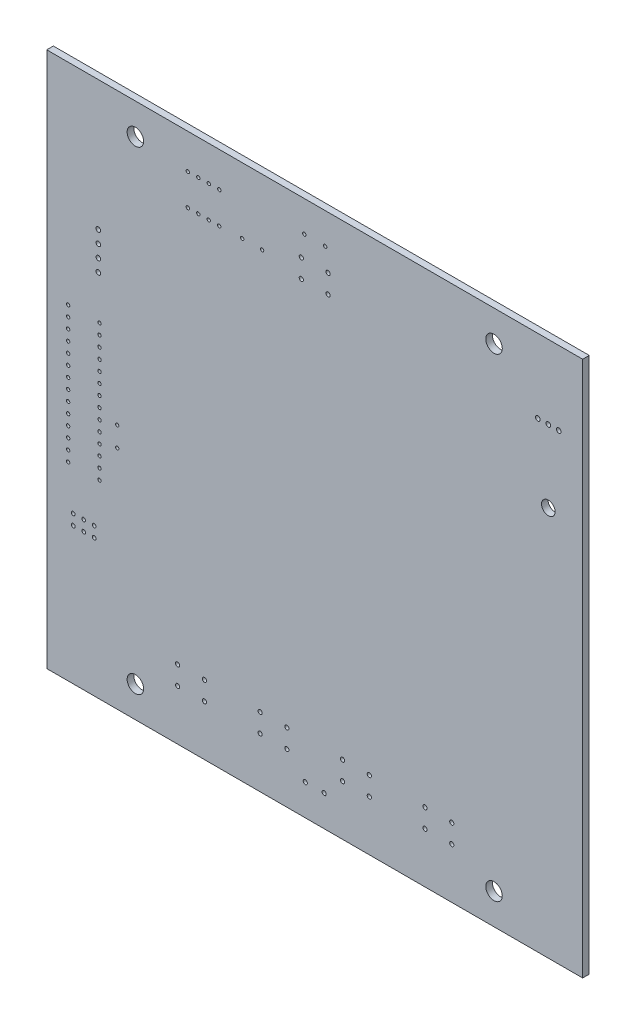
SolidWorks part; units mm, degrees
ref_plane "Ebene vorne" through (0, 0, 0) normal (0, 0, 1) x (1, 0, 0)
ref_plane "Ebene oben" through (0, 0, 0) normal (0, 1, 0) x (1, 0, 0)
ref_plane "Ebene rechts" through (0, 0, 0) normal (1, 0, 0) x (0, 0, -1)
ref_plane "Dielectric_Layer Layer 1" through (0, 0, 1.6) normal (0, 0, 1) x (1, 0, 0)
sketch "Skizze1" plane through (0, 0, 0) normal (0, 0, 1) x (1, 0, 0)
  line L0 (2.5, 2.5) -> (132.5, 2.5)
  line L1 (132.5, 2.5) -> (132.5, 132.5)
  line L2 (132.5, 132.5) -> (2.5, 132.5)
  line L3 (2.5, 132.5) -> (2.5, 2.5)
extrude "Board_Outline" add sketch "Skizze1" along normal blind 1.6 separate body
sketch "Skizze2" plane through (0, 0, 0) normal (0, 0, 1) x (1, 0, 0)
  circle A0 centre (24, 125) radius 2
  circle A1 centre (111, 10) radius 2
  circle A2 centre (24, 10) radius 2
  circle A3 centre (111, 125) radius 2
  circle A4 centre (124.17, 97.094) radius 1.651
extrude "NPTH" cut sketch "Skizze2" along normal through all
sketch "Skizze3" plane through (0, 0, 0) normal (0, 0, 1) x (1, 0, 0)
  circle A0 centre (15.31, 81.51) radius 0.405
  circle A1 centre (15.31, 78.97) radius 0.405
  circle A2 centre (15.31, 76.43) radius 0.405
  circle A3 centre (15.31, 73.89) radius 0.405
  circle A4 centre (15.31, 71.35) radius 0.405
  circle A5 centre (15.31, 68.81) radius 0.405
  circle A6 centre (15.31, 66.27) radius 0.405
  circle A7 centre (15.31, 63.73) radius 0.405
  circle A8 centre (15.31, 61.19) radius 0.405
  circle A9 centre (15.31, 58.65) radius 0.405
  circle A10 centre (15.31, 56.11) radius 0.405
  circle A11 centre (15.31, 53.57) radius 0.405
  circle A12 centre (15.31, 51.03) radius 0.405
  circle A13 centre (15.31, 48.49) radius 0.405
  circle A14 centre (7.69, 48.49) radius 0.405
  circle A15 centre (7.69, 51.03) radius 0.405
  circle A16 centre (7.69, 53.57) radius 0.405
  circle A17 centre (7.69, 56.11) radius 0.405
  circle A18 centre (7.69, 58.65) radius 0.405
  circle A19 centre (7.69, 61.19) radius 0.405
  circle A20 centre (7.69, 63.73) radius 0.405
  circle A21 centre (7.69, 66.27) radius 0.405
  circle A22 centre (7.69, 68.81) radius 0.405
  circle A23 centre (7.69, 71.35) radius 0.405
  circle A24 centre (7.69, 73.89) radius 0.405
  circle A25 centre (7.69, 76.43) radius 0.405
  circle A26 centre (7.69, 78.97) radius 0.405
  circle A27 centre (7.69, 81.51) radius 0.405
  circle A28 centre (64.96, 125) radius 0.405
  circle A29 centre (70.04, 125) radius 0.405
  circle A30 centre (15.01, 92) radius 0.56
  circle A31 centre (15, 101) radius 0.56
  circle A32 centre (15.02, 95) radius 0.56
  circle A33 centre (15.01, 98.01) radius 0.56
  circle A34 centre (19.59, 62.2) radius 0.405
  circle A35 centre (19.59, 57.38) radius 0.405
  circle A36 centre (121.63, 114.62) radius 0.56
  circle A37 centre (124.17, 114.62) radius 0.56
  circle A38 centre (126.71, 114.62) radius 0.56
  circle A39 centre (54.74, 116.59) radius 0.405
  circle A40 centre (49.92, 116.59) radius 0.405
  circle A41 centre (44.34, 116.42) radius 0.405
  circle A42 centre (41.8, 116.42) radius 0.405
  circle A43 centre (39.26, 116.42) radius 0.405
  circle A44 centre (36.72, 116.42) radius 0.405
  circle A45 centre (36.72, 124.04) radius 0.405
  circle A46 centre (39.26, 124.04) radius 0.405
  circle A47 centre (41.8, 124.04) radius 0.405
  circle A48 centre (44.34, 124.04) radius 0.405
  circle A49 centre (70.75, 119.76) radius 0.51
  circle A50 centre (64.25, 119.76) radius 0.51
  circle A51 centre (70.75, 115.24) radius 0.51
  circle A52 centre (64.25, 115.24) radius 0.51
  circle A53 centre (34.25, 14.74) radius 0.51
  circle A54 centre (40.75, 14.74) radius 0.51
  circle A55 centre (34.25, 19.26) radius 0.51
  circle A56 centre (40.75, 19.26) radius 0.51
  circle A57 centre (54.25, 14.74) radius 0.51
  circle A58 centre (60.75, 14.74) radius 0.51
  circle A59 centre (54.25, 19.26) radius 0.51
  circle A60 centre (60.75, 19.26) radius 0.51
  circle A61 centre (74.25, 14.74) radius 0.51
  circle A62 centre (80.75, 14.74) radius 0.51
  circle A63 centre (74.25, 19.26) radius 0.51
  circle A64 centre (80.75, 19.26) radius 0.51
  circle A65 centre (94.25, 14.74) radius 0.51
  circle A66 centre (100.75, 14.74) radius 0.51
  circle A67 centre (94.25, 19.26) radius 0.51
  circle A68 centre (100.75, 19.26) radius 0.51
  circle A69 centre (65.21, 10) radius 0.51
  circle A70 centre (69.79, 10) radius 0.51
  circle A71 centre (8.92, 38.29) radius 0.455
  circle A72 centre (8.92, 35.75) radius 0.455
  circle A73 centre (11.46, 38.29) radius 0.455
  circle A74 centre (11.46, 35.75) radius 0.455
  circle A75 centre (14, 38.29) radius 0.455
  circle A76 centre (14, 35.75) radius 0.455
extrude "PTH" cut sketch "Skizze3" along normal through all
